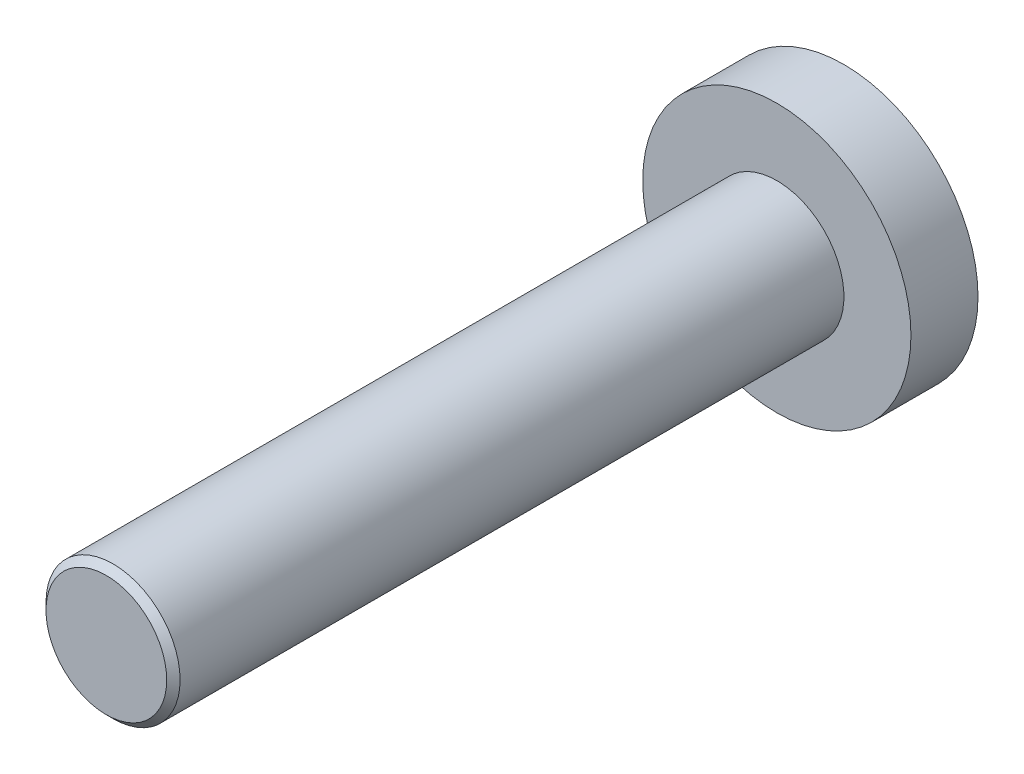
SolidWorks part; units mm, degrees
material "AISI 1020"
ref_plane "前视基准面" through (0, 0, 0) normal (0, 0, 1) x (1, 0, 0)
ref_plane "上视基准面" through (0, 0, 0) normal (0, 1, 0) x (1, 0, 0)
ref_plane "右视基准面" through (0, 0, 0) normal (1, 0, 0) x (0, 0, -1)
sketch "草图1" plane through (0, 0, 0) normal (0, 0, 1) x (1, 0, 0)
  circle A0 centre (0, 0) radius 2
  dimension "D1" = 4
extrude "拉伸1" add sketch "草图1" along normal blind 20
sketch "草图2" plane through (0, 0, 0) normal (0, 0, -1) x (-1, 0, 0)
  circle A0 centre (0, 0) radius 4
  dimension "D1" = 8
extrude "拉伸2" add sketch "草图2" along normal blind 2
chamfer "倒角1" distance 0.2 angle 45 1 edges at (2, 0, 20)
